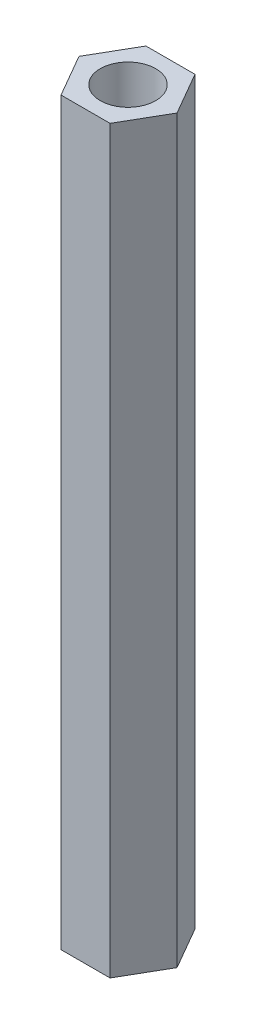
SolidWorks part; units mm, degrees
material "黄铜"
ref_plane "前视基准面" through (0, 0, 0) normal (0, 0, 1) x (1, 0, 0)
ref_plane "上视基准面" through (0, 0, 0) normal (0, 1, 0) x (1, 0, 0)
ref_plane "右视基准面" through (0, 0, 0) normal (1, 0, 0) x (0, 0, -1)
sketch "草图1" plane through (0, 0, 0) normal (0, 1, 0) x (1, 0, 0)
  line L1 (2.65, 0) -> (1.325, 2.295)
  line L2 (1.325, 2.295) -> (-1.325, 2.295)
  line L3 (-1.325, 2.295) -> (-2.65, 0)
  line L4 (-2.65, 0) -> (-1.325, -2.295)
  line L5 (-1.325, -2.295) -> (1.325, -2.295)
  line L6 (1.325, -2.295) -> (2.65, 0)
  circle A1 centre (0, 0) radius 2.295 construction
extrude "凸台-拉伸1" add sketch "草图1" along normal blind 40
sketch "草图3" plane through (0, 40, 0) normal (0, 1, 0) x (1, 0, 0)
  circle A0 centre (0, 0) radius 1.5
extrude "切除-拉伸1" cut sketch "草图3" against normal blind 40
